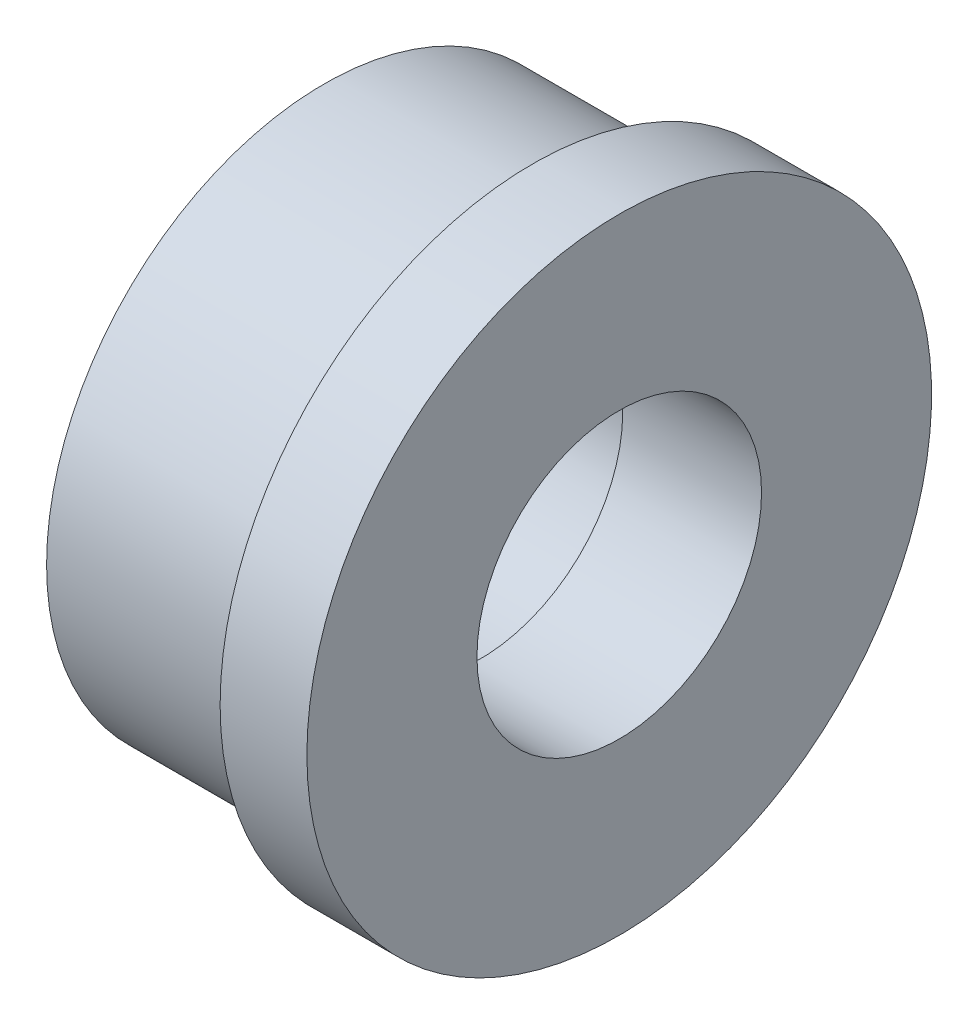
SolidWorks part; units mm, degrees
ref_plane "Front Plane" through (0, 0, 0) normal (0, 0, 1) x (1, 0, 0)
ref_plane "Top Plane" through (0, 0, 0) normal (0, 1, 0) x (1, 0, 0)
ref_plane "Right Plane" through (0, 0, 0) normal (1, 0, 0) x (0, 0, -1)
sketch "Sketch1" plane through (0, 0, 0) normal (0, 0, 1) x (1, 0, 0)
  line L0 (0, 0) -> (5.1881, 0) construction
  line L2 (-4.25, -1.875) -> (-4.25, 9) construction
  line L3 (-4.25, 9) -> (4.25, 9)
  line L4 (4.25, 4.1) -> (4.25, 9)
  line L5 (-4.25, 9) -> (-4.25, 4.15)
  line L6 (-4.25, 4.15) -> (0.25, 4.15)
  line L8 (0.25, 4.1) -> (4.25, 4.1)
  line L11 (0.25, 4.15) -> (0.25, 4.1)
  dimension "D1" = 9
  dimension "D2" = 8.5
  dimension "D3" = 4.15
  dimension "D4" = 4.25
  dimension "D5" = 4.1
  dimension "D6" = 4
revolve "Revolve1" add sketch "Sketch1" angle 360 about L0
sketch "Sketch2" plane through (0, 0, 0) normal (0, 0, 1) x (1, 0, 0)
  line L6 (0, 0) -> (5.4705, 0) construction
  line L7 (1.75, 8) -> (-4.25, 8)
  line L9 (4.25, 3.3693) -> (4.25, 9) construction
  line L10 (4.25, 9) -> (1.75, 9) construction
  line L11 (1.75, 9) -> (1.75, 8) construction
  line L12 (1.75, 8) -> (-4.25, 8) construction
  line L13 (-4.25, 8) -> (-4.25, 3.3693) construction
  line L14 (4.25, 9) -> (-4.25, 9) construction
  line L15 (4.25, -9) -> (4.25, 9) construction
  line L16 (-4.25, 9) -> (-4.25, -9) construction
  line L17 (1.75, 8) -> (1.75, 9)
  line L18 (1.75, 9) -> (-4.25, 9)
  line L19 (-4.25, 8) -> (-4.25, 9)
  dimension "D1" = 8
  dimension "D2" = 6
revolve "Cut-Revolve1" cut sketch "Sketch2" angle 360 about L6
